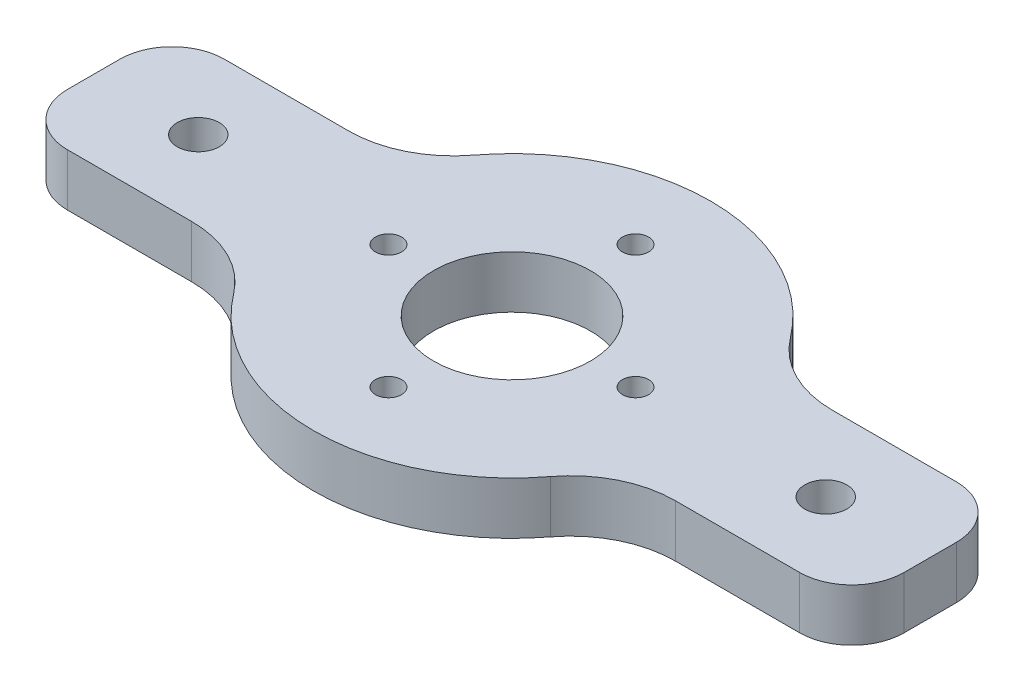
SolidWorks part; units mm, degrees
material "6061 Alloy"
ref_plane "Front Plane" through (0, 0, 0) normal (0, 0, 1) x (1, 0, 0)
ref_plane "Top Plane" through (0, 0, 0) normal (0, 1, 0) x (1, 0, 0)
ref_plane "Right Plane" through (0, 0, 0) normal (1, 0, 0) x (0, 0, -1)
sketch "Sketch1" plane through (0, 0, 0) normal (0, 1, 0) x (1, 0, 0)
  line L0 (0, 24.13) -> (0, -24.13) construction
  line L1 (-44.45, 9.525) -> (44.45, 9.525)
  line L2 (-50.8, 3.175) -> (-50.8, -3.175)
  line L3 (-44.45, -9.525) -> (44.45, -9.525)
  line L4 (50.8, 3.175) -> (50.8, -3.175)
  line L5 (-50.8, 9.525) -> (50.8, -9.525) construction
  line L6 (-50.8, -9.525) -> (50.8, 9.525) construction
  line L7 (-50.8, 0) -> (50.8, 0) construction
  circle A0 centre (0, 0) radius 15 construction
  circle A1 centre (0, 0) radius 9.525
  circle A2 centre (0, 0) radius 24.13
  circle A3 centre (15, 0) radius 1.5875
  circle A4 centre (0, -15) radius 1.5875
  circle A5 centre (-15, 0) radius 1.5875
  circle A6 centre (0, 15) radius 1.5875
  arc A7 (-29.3683, 9.525) -> (-19.2413, 14.5612) centre (-29.3683, 22.225) ccw
  arc A8 (-29.3683, -9.525) -> (-19.2413, -14.5612) centre (-29.3683, -22.225) cw
  arc A9 (29.3683, -9.525) -> (19.2413, -14.5612) centre (29.3683, -22.225) ccw
  arc A10 (29.3683, 9.525) -> (19.2413, 14.5612) centre (29.3683, 22.225) cw
  arc A11 (44.45, -9.525) -> (50.8, -3.175) centre (44.45, -3.175) ccw
  arc A12 (44.45, 9.525) -> (50.8, 3.175) centre (44.45, 3.175) cw
  arc A13 (-44.45, -9.525) -> (-50.8, -3.175) centre (-44.45, -3.175) cw
  arc A14 (-44.45, 9.525) -> (-50.8, 3.175) centre (-44.45, 3.175) ccw
  circle A15 centre (-38.1, 0) radius 2.5527
  circle A16 centre (38.1, 0) radius 2.5527
  point P16 (0, 0)
  dimension "D1" = 30
  dimension "D2" = 19.05
  dimension "D3" = 48.26
  dimension "D4" = 3.175
  dimension "D8" = 12.7
  dimension "D9" = 6.35
  dimension "D10" = 5.1054
  dimension "D6" = 19.05
  dimension "D7" = 101.6
  dimension "D11" = 38.1
  dimension "D5" = 4
extrude "Boss-Extrude2" add sketch "Sketch1" along normal blind 6.35 contours L1 A2 L3 A1 A5 | L3 A2 L1 A1 A3 | L3 A2 A4 | L1 A2 A6 | L1 A14 L2 A13 L3 A2 A15 | A12 L1 A2 L3 A11 L4 A16 | A7 L1 A2 | L3 A8 A2 | L1 A10 A2 | A9 L3 A2
